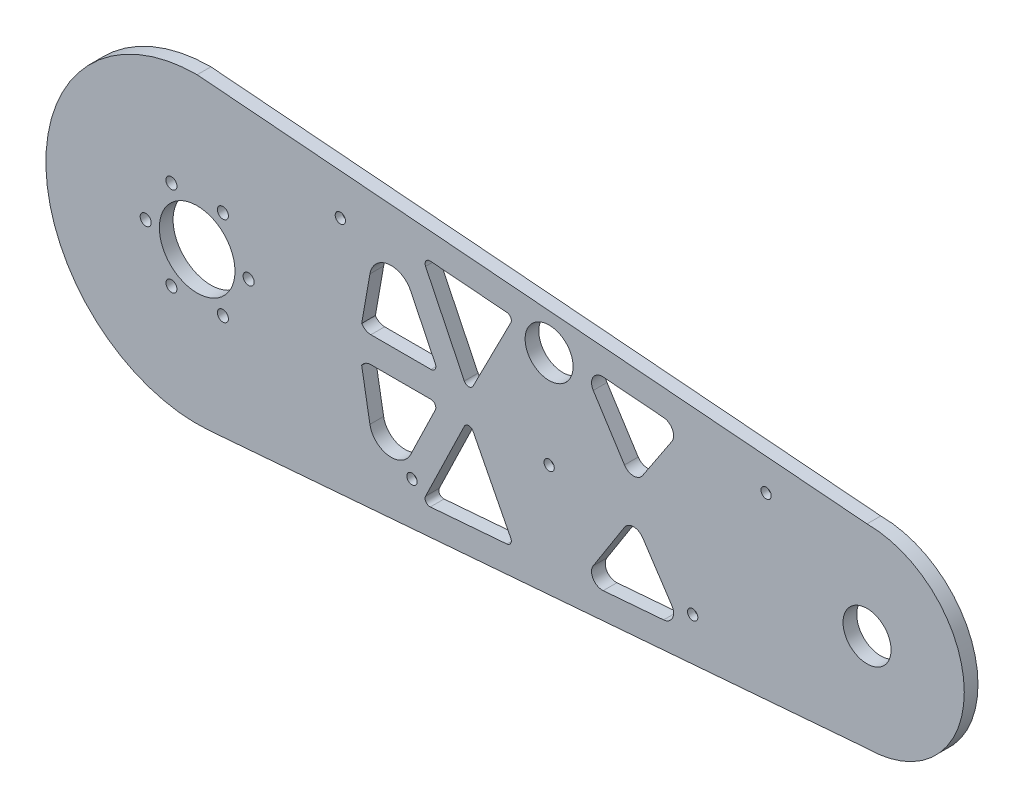
SolidWorks part; units mm, degrees
other "Marca1"
sketch "Croquis3" plane through (-70, -70, 6.35) normal (0, 0, 1) x (1, 0, 0)
material "6061-O (SS)"
ref_plane "Front Plane" through (0, 0, 0) normal (0, 0, 1) x (1, 0, 0)
ref_plane "Top Plane" through (0, 0, 0) normal (0, 1, 0) x (1, 0, 0)
ref_plane "Right Plane" through (0, 0, 0) normal (1, 0, 0) x (0, 0, -1)
sketch "Sketch1" plane through (0, 0, 0) normal (0, 0, 1) x (1, 0, 0)
  line L0 (0, 70) -> (310, 45)
  line L1 (5.1714, -69.8087) -> (310, -45)
  line L2 (0, 0) -> (310, 0) construction
  line L3 (107.899, 49.2595) -> (143.3142, 46.4034)
  line L4 (80.3974, 6) -> (108.2029, 6)
  line L5 (219.6238, 32.8105) -> (206.1309, 12.4175)
  line L6 (197.7459, 12.4871) -> (183.2969, 35.1335)
  line L7 (162.8785, 6) -> (162.8785, -6) construction
  line L8 (258.6323, 64.5867) -> (258.6323, 39.5867) construction
  line L9 (145.1311, 43.1448) -> (127.6579, 9.0076)
  line L10 (123.6419, 9.0508) -> (105.6999, 46.044)
  line L11 (103.9873, 49.575) -> (42.0027, 49.575) construction
  line L12 (187.9139, 42.8067) -> (215.8558, 40.5533)
  line L13 (162.8785, 44.8257) -> (162.8785, 6) construction
  line L14 (67.1248, 64.5867) -> (162.8785, 40) construction
  line L15 (201.8849, 6) -> (201.8849, 41.68) construction
  line L16 (125.6066, 5) -> (125.6066, 47.8315) construction
  line L17 (98.7899, 32.7928) -> (110.2216, 9.2228)
  line L18 (125.6066, -5) -> (125.6066, -47.8315) construction
  line L19 (201.8849, -6) -> (201.8849, -41.68) construction
  line L20 (162.8785, -44.8257) -> (162.8785, -6) construction
  line L21 (103.9873, -49.575) -> (42.0027, -49.575) construction
  line L22 (98.7899, -32.7928) -> (110.2216, -9.2228)
  line L23 (67.1248, 64.5867) -> (409.6974, 64.5867) construction
  line L24 (187.9139, -42.8067) -> (215.8558, -40.5533)
  line L25 (123.6419, -9.0508) -> (105.6999, -46.044)
  line L26 (145.1311, -43.1448) -> (127.6579, -9.0076)
  line L27 (162.8785, 0) -> (258.6323, 64.5867) construction
  line L28 (67.1248, 64.5867) -> (67.1248, 39.5867) construction
  line L29 (197.7459, -12.4871) -> (183.2969, -35.1335)
  line L30 (219.6238, -32.8105) -> (206.1309, -12.4175)
  line L31 (80.3974, -6) -> (108.2029, -6)
  line L32 (107.899, -49.2595) -> (143.3142, -46.4034)
  line L33 (0, -6.35) -> (0, 6.35) construction
  line L34 (67.1248, 39.5867) -> (162.8785, 40) construction
  line L35 (162.8785, 40) -> (68.3705, 24.1395) construction
  line L36 (79.9417, 30.1512) -> (76.1361, 8.3844)
  line L37 (79.9417, -30.1512) -> (76.1361, -8.3844)
  arc A0 (76.1361, 8.3844) -> (80.3974, 6) centre (80.3974, 11) ccw
  arc A1 (310, -45) -> (310, 45) centre (310, 0) ccw
  circle A2 centre (0, 0) radius 14.2938
  circle A3 centre (310, 0) radius 11.115
  arc A4 (79.9417, 30.1512) -> (98.7899, 32.7928) centre (89.7923, 28.4289) cw
  arc A5 (98.7899, -32.7928) -> (79.9417, -30.1512) centre (89.7923, -28.4289) cw
  arc A6 (0, 70) -> (5.1714, -69.8087) centre (0, 0) ccw
  arc A7 (187.9139, 42.8067) -> (183.2969, 35.1335) centre (187.512, 37.8229) ccw
  arc A8 (219.6238, 32.8105) -> (215.8558, 40.5533) centre (215.4539, 35.5695) ccw
  arc A9 (206.1309, 12.4175) -> (197.7459, 12.4871) centre (201.961, 15.1765) cw
  circle A10 centre (162.8785, 40) radius 11.1125
  arc A13 (108.2029, 6) -> (110.2216, 9.2228) centre (108.2029, 8.2436) ccw
  arc A14 (123.6419, 9.0508) -> (127.6579, 9.0076) centre (125.6607, 10.0299) ccw
  arc A15 (145.1311, 43.1448) -> (143.3142, 46.4034) centre (143.1339, 44.1671) ccw
  arc A16 (107.899, 49.2595) -> (105.6999, 46.044) centre (107.7186, 47.0231) ccw
  arc A17 (107.899, -49.2595) -> (105.6999, -46.044) centre (107.7186, -47.0231) cw
  arc A18 (145.1311, -43.1448) -> (143.3142, -46.4034) centre (143.1339, -44.1671) cw
  arc A19 (123.6419, -9.0508) -> (127.6579, -9.0076) centre (125.6607, -10.0299) cw
  arc A20 (108.2029, -6) -> (110.2216, -9.2228) centre (108.2029, -8.2436) cw
  arc A24 (206.1309, -12.4175) -> (197.7459, -12.4871) centre (201.961, -15.1765) ccw
  arc A25 (219.6238, -32.8105) -> (215.8558, -40.5533) centre (215.4539, -35.5695) cw
  arc A26 (187.9139, -42.8067) -> (183.2969, -35.1335) centre (187.512, -37.8229) cw
  arc A29 (76.1361, -8.3844) -> (80.3974, -6) centre (80.3974, -11) cw
  point P31 (177.8851, 43.6155)
  point P42 (187.6504, 6)
  point P44 (85.2753, 60.6574)
  point P45 (138.1067, 6)
  point P79 (85.2753, -60.6574)
  point P100 (138.1067, -6)
  point P101 (187.6504, -6)
  point P102 (177.8851, -43.6155)
  point P104 (0, 0)
  point P114 (310, 0)
  point P119 (0.2114, 0.3175)
  dimension "D2" = 45
  dimension "D3" = 12.7
  dimension "D4" = 22.23
  dimension "D6" = 12
  dimension "D11" = 5
  dimension "D12" = 70
  dimension "D13" = 25
  dimension "D8" = 5
  dimension "D14" = 12
  dimension "D15" = 25
  dimension "D16" = 310
  dimension "D17" = 22.225
  dimension "D5" = 28.5877
  dimension "D19" = 10
  dimension "D20" = 10
  dimension "D7" = 6
  dimension "D9" = 9.279
  dimension "D10" = 34
  dimension "D18" = 40
extrude "Boss-Extrude1" add sketch "Sketch1" along normal blind 6.35
sketch "Sketch2" plane through (0, 0, 6.35) normal (0, 0, 1) x (1, 0, 0)
  line L0 (263.0927, 39.4927) -> (-0.4655, 64.9983)
  line L1 (4.6885, -64.8307) -> (263.1366, -39.5384)
  arc A0 (-0.4655, 64.9983) -> (4.6885, -64.8307) centre (0, 0) ccw
  arc A1 (263.1366, -39.5384) -> (270.3186, -23.7999) centre (262.1626, -29.5859) ccw
  circle A2 centre (0, 0) radius 40
  arc A3 (270.292, 23.7623) -> (270.3186, -23.7999) centre (303.867, 0) ccw
  arc A4 (270.292, 23.7623) -> (263.0927, 39.4927) centre (262.1295, 29.5392) ccw
  dimension "D1" = 10
  dimension "D2" = 41.133
  dimension "D3" = 65
ref_plane "Plane1" through (0, 0, 10) normal (0, 0, 1) x (1, 0, 0)
sketch "Croquis1" plane through (0, 0, 6.35) normal (0, 0, 1) x (1, 0, 0)
  line L0 (5.1714, -69.8087) -> (310, -45) construction
  line L1 (99.4174, -42.273) -> (229.2992, -31.7024) construction
  line L9 (103.0721, -23.9638) -> (88.7465, -42.3671) construction
  line L10 (98.7899, -32.7928) -> (110.2216, -9.2228) construction
  circle A1 centre (99.4174, -42.273) radius 2.3813
  circle A2 centre (229.2992, -31.7024) radius 2.3813
  point P20 (0, 0)
  dimension "D5" = 4.7625
  dimension "D1" = 4.7625
  dimension "D2" = 19.8
extrude "Cortar-Extruir1" cut sketch "Croquis1" against normal blind 50
sketch "Croquis2" plane through (0, 0, 6.35) normal (0, 0, 1) x (1, 0, 0)
  circle A0 centre (99.4174, -42.273) radius 5
  circle A1 centre (229.2992, -31.7024) radius 5
  dimension "D1" = 10
sketch "Croquis4" plane through (0, 0, 6.35) normal (0, 0, 1) x (1, 0, 0)
  line L0 (162.8785, 40) -> (162.8785, -40) construction
  line L1 (135.7539, -40) -> (190.0032, -40) construction
  circle A0 centre (162.8785, 0) radius 5
  point P8 (162.8785, -40)
  dimension "D1" = 10
  dimension "D2" = 40
sketch "Croquis6" plane through (0, 0, 6.35) normal (0, 0, 1) x (1, 0, 0)
  line L0 (99.4174, -42.273) -> (229.2992, -31.7024) construction
  line L1 (229.2992, -31.7024) -> (263.2934, 34.0273) construction
  line L2 (99.4174, -42.273) -> (66.2632, 45.6861) construction
  circle A0 centre (66.2632, 45.6861) radius 2.3813
  circle A1 centre (263.2934, 34.0273) radius 2.3813
  dimension "D5" = 4.7625
  dimension "D1" = 94
  dimension "D2" = 74
  dimension "D3" = 106
  dimension "D4" = 238
extrude "Cortar-Extruir6" cut sketch "Croquis6" against normal blind 10
sketch "Croquis7" plane through (0, 0, 6.35) normal (0, 0, 1) x (1, 0, 0)
  circle A0 centre (66.2632, 45.6861) radius 5
  circle A1 centre (263.2934, 34.0273) radius 5
  dimension "D1" = 10
sketch "Croquis8" plane through (0, 0, 6.35) normal (0, 0, 1) x (1, 0, 0)
  circle A0 centre (0, 0) radius 17.5
  dimension "D1" = 35
extrude "Cortar-Extruir8" cut sketch "Croquis8" against normal blind 10
sketch "Croquis9" plane through (0, 0, 0) normal (0, 0, -1) x (-1, 0, 0)
  line L0 (0, 0) -> (23.8125, 0) construction
  circle A0 centre (0, 0) radius 23.8125 construction
  circle A1 centre (23.8125, 0) radius 2.5527
  circle A2 centre (11.9062, -20.6222) radius 2.5527
  circle A3 centre (-11.9063, -20.6222) radius 2.5527
  circle A4 centre (-23.8125, 0) radius 2.5527
  circle A5 centre (-11.9062, 20.6222) radius 2.5527
  circle A6 centre (11.9063, 20.6222) radius 2.5527
  point P17 (0, 0)
  dimension "D1" = 47.625
  dimension "D2" = 5.1054
  dimension "D3" = 6
extrude "Cortar-Extruir9" cut sketch "Croquis9" against normal blind 10
sketch "Croquis5" plane through (0, 0, 6.35) normal (0, 0, 1) x (1, 0, 0)
  circle A0 centre (162.8785, -5) radius 2.3813
  dimension "D1" = 4.7625
extrude "Cortar-Extruir5" cut sketch "Croquis5" against normal blind 10
sketch "Croquis10" plane through (0, 0, 0) normal (0, 0, -1) x (-1, 0, 0)
  circle A0 centre (-263.2934, 34.0273) radius 5
  circle A1 centre (-66.2632, 45.6861) radius 5
  circle A3 centre (-229.2992, -31.7024) radius 5
  circle A4 centre (-99.4174, -42.273) radius 5
  circle A5 centre (-162.8785, -5) radius 5
  dimension "D1" = 10
  dimension "D2" = 10
extrude "Cortar-Extruir10" cut sketch "Croquis10" against normal blind 3.18
